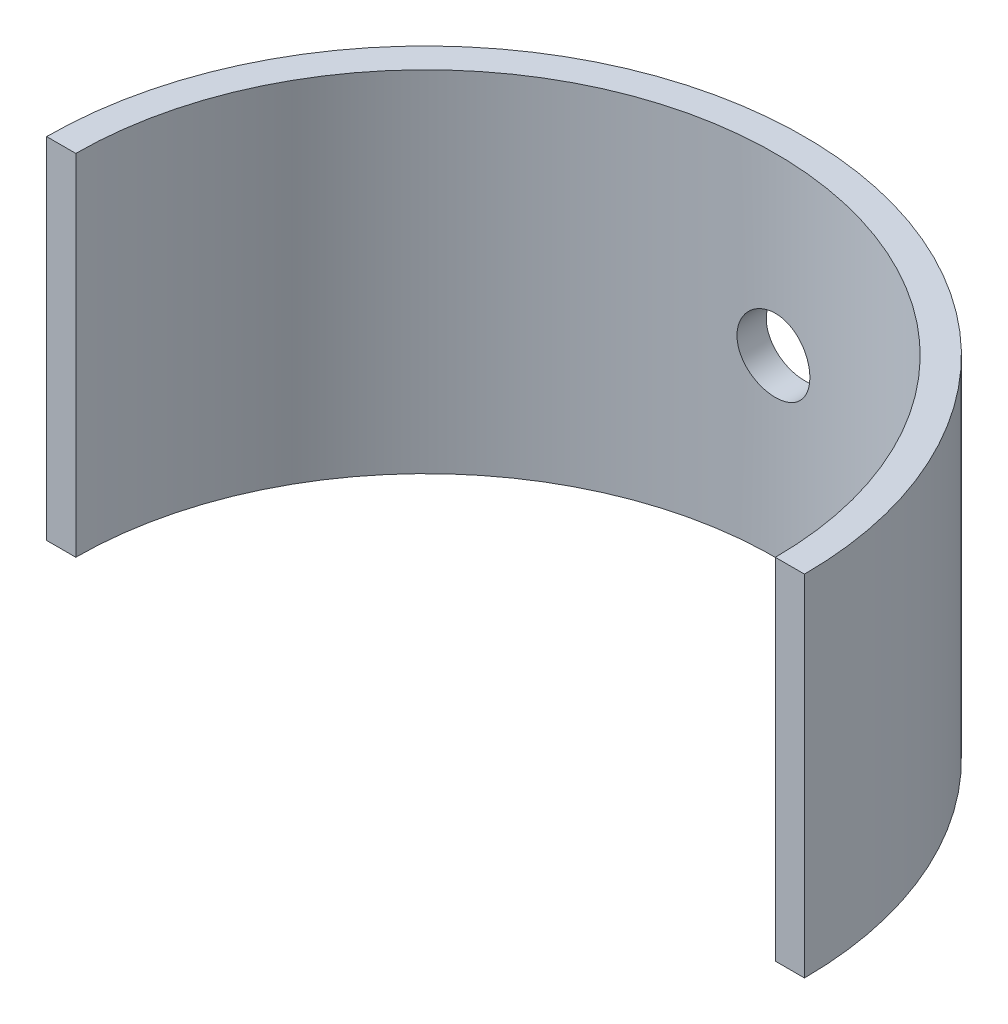
SolidWorks part; units mm, degrees
ref_plane "前视基准面" through (0, 0, 0) normal (0, 0, 1) x (1, 0, 0)
ref_plane "上视基准面" through (0, 0, 0) normal (0, 1, 0) x (1, 0, 0)
ref_plane "右视基准面" through (0, 0, 0) normal (1, 0, 0) x (0, 0, -1)
other "Configuration Table"
sketch "草图1" plane through (0, 0, 0) normal (0, 1, 0) x (1, 0, 0)
  line L0 (0, 24.8116) -> (0, -38.8406) construction
  line L1 (-26, 0) -> (-24, 0)
  line L2 (24, 0) -> (26, 0)
  arc A0 (-24, 0) -> (24, 0) centre (0, 0) cw
  arc A1 (-26, 0) -> (26, 0) centre (0, 0) cw
  dimension "D1" = 24
  dimension "D2" = 26
extrude "凸台-拉伸1" add sketch "草图1" along normal blind 24
sketch "草图2" plane through (0, 0, 0) normal (0, 0, 1) x (1, 0, 0)
  line L0 (0, 25.1097) -> (0, -6.4606) construction
  circle A0 centre (0, 12) radius 2.5
  point P3 (0, 12)
  point P9 (0, 12)
  point P11 (0, 12)
  dimension "D2" = 5
  dimension "D1" = 12
hole_wizard "Ø5.0 (5) 直径孔1" positions "草图2" profile "草图4" hole size "Ø5.0" standard "GB" end condition through all
sketch "草图4" plane through (0, 12, 0) normal (1, 0, 0) x (0, -1, 0)
  line L0 (0, 0) -> (0, 26)
  line L1 (0, 26) -> (2.5, 26)
  line L2 (2.5, 26) -> (2.5, 0.025)
  line L3 (2.5, 0.025) -> (2.525, 0)
  line L5 (2.525, 0) -> (0, 0)
  line L6 (-2.5, 0.025) -> (-2.525, 0) construction
  line L11 (0, -6.35) -> (0, 107.95) construction
  dimension "通孔孔直径" = 5
  dimension "通孔孔深度" = 26
  dimension "近端锥形沉头孔直径" = 5.05
  dimension "近端锥形沉头孔角度" = 90
